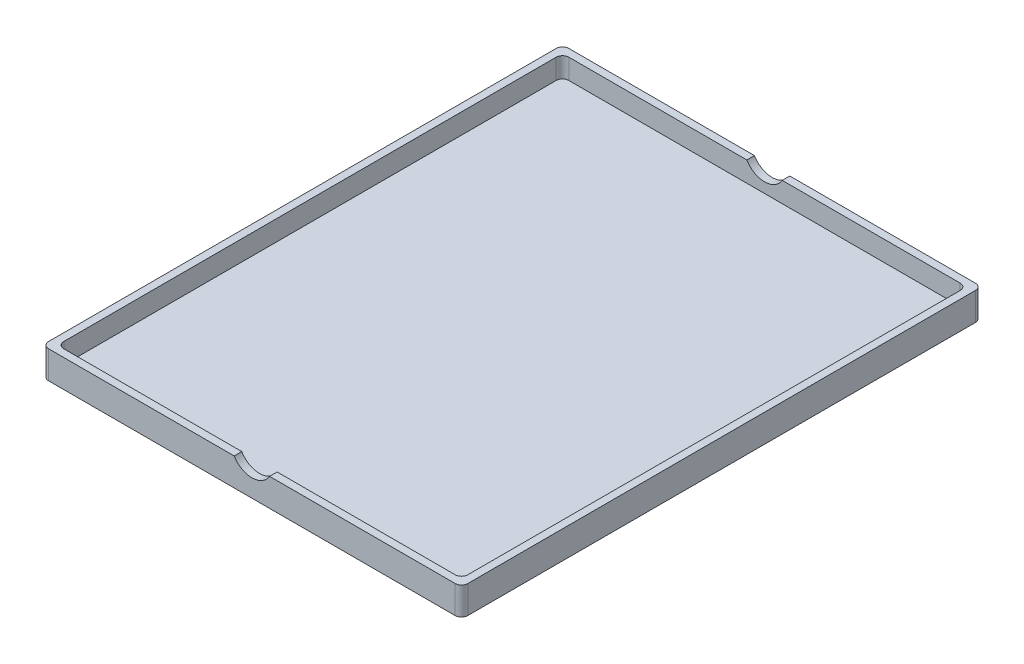
SolidWorks part; units mm, degrees
ref_plane "Front Plane" through (0, 0, 0) normal (0, 0, 1) x (1, 0, 0)
ref_plane "Top Plane" through (0, 0, 0) normal (0, 1, 0) x (1, 0, 0)
ref_plane "Right Plane" through (0, 0, 0) normal (1, 0, 0) x (0, 0, -1)
sketch "Sketch1" plane through (0, 0, 0) normal (0, 1, 0) x (1, 0, 0)
  line L1 (80, -100) -> (-80, -100)
  line L2 (80, -100) -> (80, 100)
  line L3 (80, 100) -> (-80, 100)
  line L4 (-80, -100) -> (-80, 100)
  line L5 (80, -100) -> (-80, 100) construction
  line L6 (80, 100) -> (-80, -100) construction
  point P0 (0, 0)
  dimension "D1" = 160
  dimension "D2" = 200
extrude "Boss-Extrude1" add sketch "Sketch1" along normal blind 8
shell "Shell1" thickness 3
sketch "Sketch2" plane through (0, -3, 0) normal (0, -1, 0) x (1, 0, 0)
  line L1 (80, -100) -> (-80, -100)
  line L2 (80, -100) -> (80, 100)
  line L3 (80, 100) -> (-80, 100)
  line L4 (-80, -100) -> (-80, 100)
  line L5 (80, -100) -> (-80, 100) construction
  line L6 (80, 100) -> (-80, -100) construction
  point P0 (0, 0)
  dimension "D1" = 160
  dimension "D2" = 200
extrude "Boss-Extrude2" add sketch "Sketch2" along normal blind 2
fillet "Fillet1" radius 2.5 12 edges at (-80, -4, -100) (80, -4, -100) (80, -4, 100) (-80, -4, 100) (-83, 2.5, -103) (83, 2.5, -103) (83, 2.5, 103) (-83, 2.5, 103) (80, 4, 100) (-80, 4, 100) (80, 4, -100) (-80, 4, -100)
sketch "Sketch5" plane through (0, 0, 103) normal (0, 0, 1) x (1, 0, 0)
  line L0 (0, 8) -> (0, -3) construction
  line L1 (-80.5, 8) -> (80.5, 8) construction
  line L2 (-80.5, -3) -> (80.5, -3) construction
  line L3 (0, 8) -> (-7, 8)
  line L4 (0, 8) -> (7, 8)
  arc A0 (-7, 8) -> (7, 8) centre (0, 12.125) ccw
  point P9 (0, 4)
  dimension "D1" = 7
  dimension "D2" = 7
  dimension "D3" = 4
extrude "Cut-Extrude4" cut sketch "Sketch5" against normal through all
